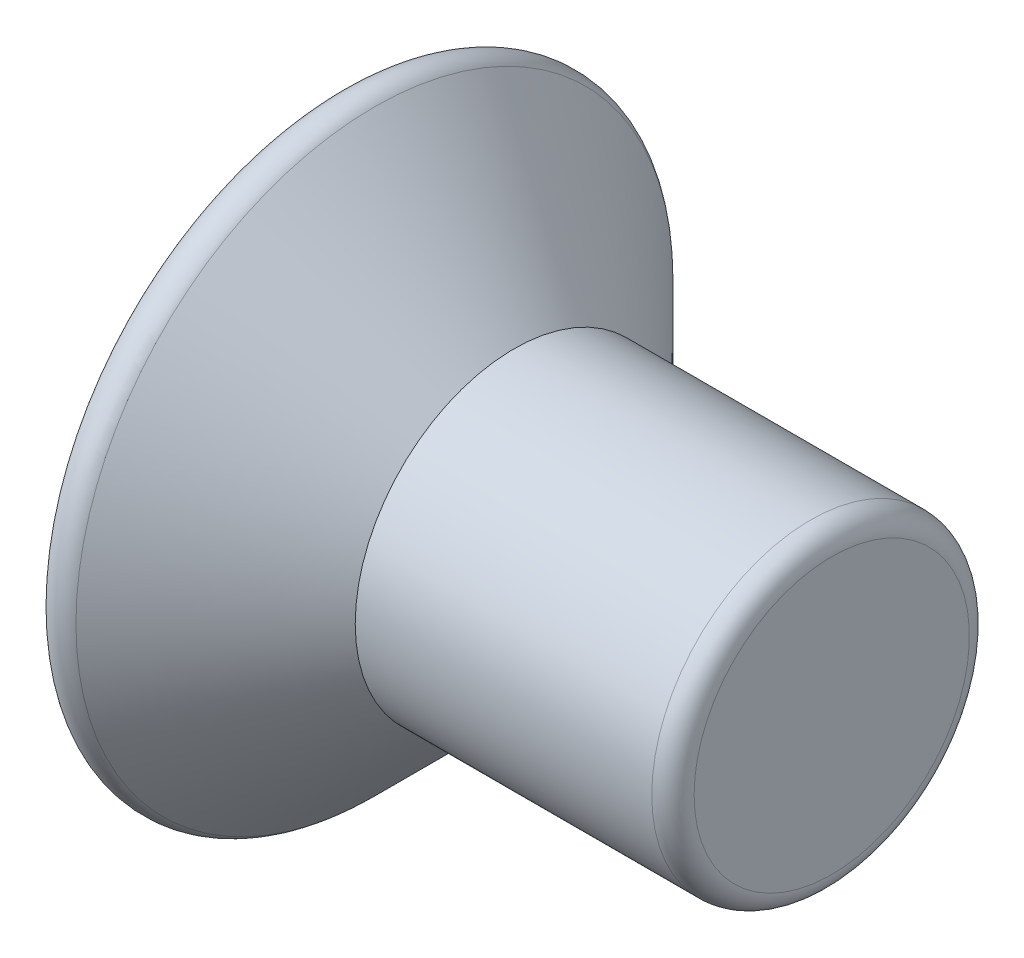
SolidWorks part; units mm, degrees
ref_plane "Plan de face" through (0, 0, 0) normal (0, 0, 1) x (1, 0, 0)
ref_plane "Plan de dessus" through (0, 0, 0) normal (0, 1, 0) x (1, 0, 0)
ref_plane "Plan de droite" through (0, 0, 0) normal (1, 0, 0) x (0, 0, -1)
sketch "Esquisse1" plane through (0, 0, 0) normal (0, 0, 1) x (1, 0, 0)
  line L0 (-5.7689, 0) -> (8.695, 0) construction
  line L1 (0, 0) -> (0, 3.16)
  line L2 (0, 3.16) -> (1.66, 1.5)
  line L3 (1.66, 1.5) -> (4.66, 1.5)
  line L4 (4.66, 1.5) -> (4.66, 0)
  line L5 (0, 0) -> (4.66, 0)
  dimension "D1" = 3.16
  dimension "D2" = 45
  dimension "D3" = 1.66
  dimension "D4" = 3
revolve "Révolution1" add sketch "Esquisse1" angle 360 about L0
sketch "Esquisse2" plane through (0, 0, 0) normal (-1, 0, 0) x (0, 0, 1)
  line L1 (0, -1.1) -> (0.9526, -0.55)
  line L2 (0.9526, -0.55) -> (0.9526, 0.55)
  line L3 (0.9526, 0.55) -> (0, 1.1)
  line L4 (0, 1.1) -> (-0.9526, 0.55)
  line L5 (-0.9526, 0.55) -> (-0.9526, -0.55)
  line L6 (-0.9526, -0.55) -> (0, -1.1)
  circle A0 centre (0, 0) radius 0.9526 construction
  dimension "D1" = 2.2
extrude "Enlèv. mat.-Extru.1" cut sketch "Esquisse2" against normal blind 0.1
fillet "Congé1" radius 0.2 2 edges at (4.66, 0, 1.5) (0, 0, 3.16)
